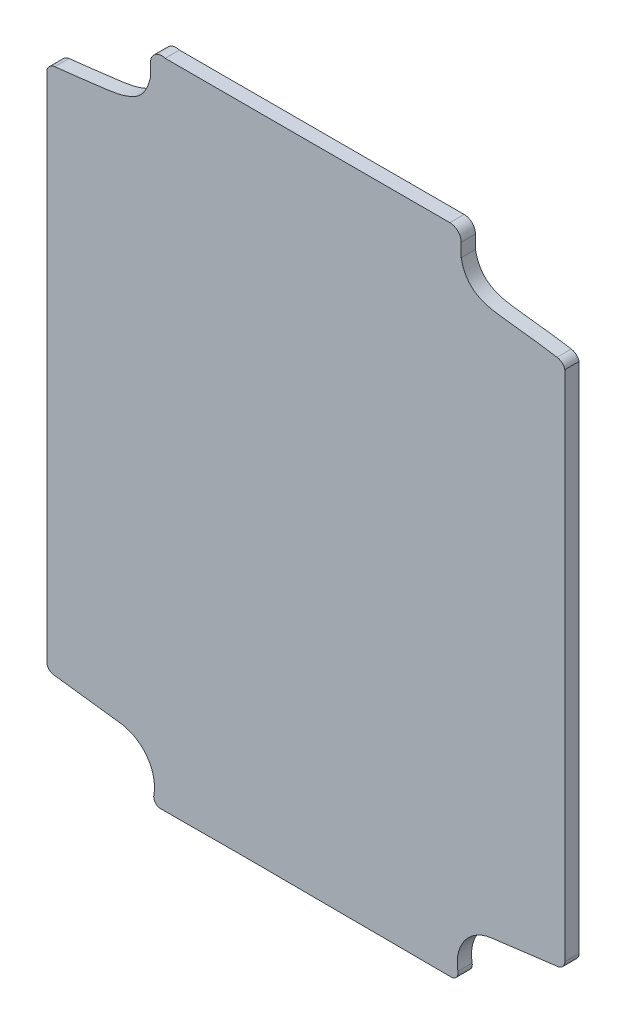
SolidWorks part; units mm, degrees
ref_plane "Front Plane" through (0, 0, 0) normal (0, 0, 1) x (1, 0, 0)
ref_plane "Top Plane" through (0, 0, 0) normal (0, 1, 0) x (1, 0, 0)
ref_plane "Right Plane" through (0, 0, 0) normal (1, 0, 0) x (0, 0, -1)
sketch "Sketch1" plane through (0, 0, 0) normal (0, 0, 1) x (1, 0, 0)
  line L0 (127, 465) -> (635, 465) construction
  line L3 (390.8841, 912.0626) -> (390.8841, 1148.9161) construction
  line L5 (213.6653, 879.6097) -> (572.9204, 879.6097)
  line L6 (587.1866, 865.3435) -> (587.1866, 848.4204)
  line L7 (717.9525, 791.5143) -> (717.9525, 144.5451)
  line L8 (708.0654, 134.658) -> (624.9414, 124.0917)
  line L9 (575.7917, 55.989) -> (311.2271, 57.05)
  line L11 (206.5649, 56.6303) -> (311.2271, 57.05)
  line L12 (74.2912, 135.2993) -> (157.4152, 124.733)
  line L13 (64.4041, 792.1556) -> (64.4041, 145.1863)
  line L14 (195.17, 865.9848) -> (195.17, 849.0616)
  line L20 (105.1835, 499.8417) -> (105.1835, 434.806) construction
  line L21 (87.257, 467.7407) -> (123.257, 467.7407) construction
  line L22 (98.7216, 499.8417) -> (111.6453, 499.8417)
  line L23 (98.7216, 434.806) -> (111.6453, 434.806)
  line L24 (111.6453, 499.8417) -> (111.6453, 484.2081)
  line L25 (98.7216, 499.8417) -> (98.7216, 484.2081)
  line L26 (98.7216, 434.806) -> (98.7216, 449.6058)
  line L27 (111.6453, 434.806) -> (111.6453, 449.6058)
  line L28 (683.0467, 434.806) -> (670.1229, 434.806)
  line L29 (683.0467, 499.8417) -> (670.1229, 499.8417)
  line L30 (683.0467, 434.806) -> (683.0467, 449.6058)
  line L31 (670.1229, 434.806) -> (670.1229, 449.6058)
  line L32 (670.1229, 499.8417) -> (670.1229, 484.2081)
  line L33 (683.0467, 499.8417) -> (683.0467, 484.2081)
  line L34 (654.6563, 466.9069) -> (698.2195, 466.9069) construction
  line L35 (423.0713, 104.5092) -> (423.0713, 91.5855)
  line L36 (358.0356, 104.5092) -> (358.0356, 91.5855)
  line L37 (423.0713, 104.5092) -> (408.2715, 104.5092)
  line L38 (423.0713, 91.5855) -> (408.2715, 91.5855)
  line L39 (358.0356, 91.5855) -> (373.6692, 91.5855)
  line L40 (358.0356, 104.5092) -> (373.6692, 104.5092)
  line L41 (423.2302, 842.8099) -> (423.2302, 829.8861)
  line L42 (358.1945, 842.8099) -> (358.1945, 829.8861)
  line L43 (423.2302, 842.8099) -> (408.4304, 842.8099)
  line L44 (423.2302, 829.8861) -> (408.4304, 829.8861)
  line L45 (358.1945, 829.8861) -> (373.8281, 829.8861)
  line L46 (358.1945, 842.8099) -> (373.8281, 842.8099)
  circle A0 centre (92.7885, 774.4272) radius 18
  circle A1 centre (153.2085, 765.7778) radius 18
  circle A2 centre (194.8311, 794.5037) radius 18
  circle A3 centre (236.8819, 848.4204) radius 18
  circle A5 centre (586.5052, 794.5037) radius 18
  circle A6 centre (628.2807, 765.7778) radius 18
  circle A7 centre (688.7549, 774.4272) radius 18
  circle A8 centre (544.9773, 848.4204) radius 18
  circle A9 centre (390.5346, 796.5425) radius 18
  circle A11 centre (92.7885, 159.2882) radius 18
  circle A12 centre (153.2085, 168.4793) radius 18
  circle A13 centre (194.8311, 139.5286) radius 18
  circle A15 centre (236.8819, 85.8518) radius 18
  circle A16 centre (544.9773, 85.8518) radius 18
  circle A17 centre (390.1739, 137.7924) radius 18
  circle A18 centre (586.5052, 139.5286) radius 18
  circle A20 centre (628.2807, 168.4793) radius 18
  circle A21 centre (688.7549, 159.2882) radius 18
  arc A22 (572.9204, 879.6097) -> (587.1866, 865.3435) centre (572.9204, 865.3435) cw
  arc A23 (708.0654, 800.1256) -> (717.9525, 791.5143) centre (706.4688, 788.3109) cw
  arc A24 (717.9525, 144.5451) -> (708.0654, 134.658) centre (708.0654, 144.5451) cw
  arc A25 (624.9414, 124.0917) -> (583.0081, 66.5315) centre (631.1129, 75.5412) ccw
  arc A26 (583.0081, 66.5315) -> (575.7917, 55.989) centre (574.1287, 64.8685) cw
  arc A27 (64.4041, 145.1863) -> (74.2912, 135.2993) centre (74.2912, 145.1863) ccw
  arc A28 (199.3485, 67.1728) -> (206.5649, 56.6303) centre (208.228, 65.5097) ccw
  arc A29 (157.4152, 124.733) -> (199.3485, 67.1728) centre (151.2437, 76.1824) cw
  arc A30 (74.2912, 800.7668) -> (64.4041, 792.1556) centre (75.8878, 788.9521) ccw
  arc A31 (213.6653, 879.6097) -> (195.17, 865.9848) centre (209.4362, 865.9848) ccw
  arc A32 (98.7216, 484.2081) -> (98.7216, 449.6058) centre (105.348, 466.9069) ccw
  arc A33 (111.6453, 484.2081) -> (111.6453, 449.6058) centre (105.0189, 466.9069) cw
  arc A34 (670.1229, 484.2081) -> (670.1229, 449.6058) centre (676.7494, 466.9069) ccw
  arc A35 (683.0467, 484.2081) -> (683.0467, 449.6058) centre (676.4202, 466.9069) cw
  circle A36 centre (148.6842, 466.9069) radius 18
  circle A37 centre (632.4423, 466.9069) radius 18
  arc A38 (373.6692, 91.5855) -> (408.2715, 91.5855) centre (390.9703, 98.2119) ccw
  arc A39 (373.6692, 104.5092) -> (408.2715, 104.5092) centre (390.9703, 97.8828) cw
  arc A40 (373.8281, 829.8861) -> (408.4304, 829.8861) centre (391.1292, 836.5126) ccw
  arc A41 (373.8281, 842.8099) -> (408.4304, 842.8099) centre (391.1292, 836.1834) cw
  spline S0 degree 3 poles (134.7471, 211.4176) (152.8168, 198.2285) (173.4297, 194.7237) (206.2799, 204.2352) (218.6001, 238.403) (215.0005, 157.9272) (261.6667, 159.9838) (283.8241, 199.2804) (314.2323, 230.1149) (305.2971, 269.6637) (285.2096, 294.946) (231.9509, 299.4798) (212.9045, 263.7426) (209.9318, 280.2662) (190.1646, 292.7397) (159.7593, 299.5382) (121.7886, 279.8173) (117.8446, 233.2785) (134.7471, 211.4176) (152.8168, 198.2285) (173.4297, 194.7237) knots -0.133764 -0.081828 -0.041908 0 0.04195 0.101208 0.155786 0.286134 0.362687 0.379278 0.452042 0.533513 0.593085 0.660805 0.699095 0.73753 0.75625 0.796881 0.866236 0.918172 0.958092 1 1.04195 1.101208 1.155786 only from (152.7697, 199.9518) to (152.7697, 199.9518)
  spline S1 degree 3 poles (135.1859, 721.7604) (153.2557, 734.9495) (173.8685, 738.4543) (206.7187, 728.9429) (219.0389, 694.7751) (215.4393, 775.2509) (262.1055, 773.1942) (284.2629, 733.8977) (314.6712, 703.0631) (305.736, 663.5143) (285.6484, 638.2321) (232.3897, 633.6982) (213.3433, 669.4354) (210.3706, 652.9118) (190.6035, 640.4383) (160.1982, 633.6398) (122.2275, 653.3608) (118.2834, 699.8995) (135.1859, 721.7604) (153.2557, 734.9495) (173.8685, 738.4543) knots -0.133764 -0.081828 -0.041908 0 0.04195 0.101208 0.155786 0.286134 0.362687 0.379278 0.452042 0.533513 0.593085 0.660805 0.699095 0.73753 0.75625 0.796881 0.866236 0.918172 0.958092 1 1.04195 1.101208 1.155786 only from (153.2085, 733.2263) to (153.2085, 733.2263)
  spline S2 degree 3 poles (645.9427, 212.0915) (627.8729, 198.9024) (607.26, 195.3976) (574.4098, 204.9091) (562.0897, 239.0769) (565.6892, 158.6011) (519.0231, 160.6577) (496.8656, 199.9543) (466.4574, 230.7889) (475.3926, 270.3377) (495.4801, 295.6199) (548.7388, 300.1538) (567.7852, 264.4165) (570.7579, 280.9402) (590.5251, 293.4137) (620.9304, 300.2122) (658.9011, 280.4912) (662.8452, 233.9524) (645.9427, 212.0915) (627.8729, 198.9024) (607.26, 195.3976) knots -0.133764 -0.081828 -0.041908 0 0.04195 0.101208 0.155786 0.286134 0.362687 0.379278 0.452042 0.533513 0.593085 0.660805 0.699095 0.73753 0.75625 0.796881 0.866236 0.918172 0.958092 1 1.04195 1.101208 1.155786 only from (627.92, 200.6257) to (627.92, 200.6257)
  spline S3 degree 3 poles (646.5422, 722.3875) (628.4724, 735.5766) (607.8596, 739.0814) (575.0094, 729.5699) (562.6892, 695.4022) (566.2888, 775.878) (519.6226, 773.8213) (497.4652, 734.5248) (467.0569, 703.6902) (475.9921, 664.1414) (496.0797, 638.8592) (549.3384, 634.3253) (568.3848, 670.0625) (571.3575, 653.5389) (591.1246, 641.0654) (621.5299, 634.2669) (659.5006, 653.9879) (663.4447, 700.5266) (646.5422, 722.3875) (628.4724, 735.5766) (607.8596, 739.0814) knots -0.133764 -0.081828 -0.041908 0 0.04195 0.101208 0.155786 0.286134 0.362687 0.379278 0.452042 0.533513 0.593085 0.660805 0.699095 0.73753 0.75625 0.796881 0.866236 0.918172 0.958092 1 1.04195 1.101208 1.155786 only from (628.5196, 733.8534) to (628.5196, 733.8534)
  spline S4 degree 3 poles (195.17, 849.0616) (190.0076, 829.9692) (180.5238, 818.7484) (154.3908, 810.5337) (101.8412, 803.5005) (88.1469, 802.6392) (74.2912, 800.7668) knots 0 0 0 0 0.202419 0.278084 0.357842 1 1 1 1
  spline S6 degree 3 poles (587.1866, 848.4204) (591.8291, 824.0333) (611.9997, 812.1812) (684.5998, 804.295) (694.2097, 801.998) (708.0654, 800.1256) knots 0 0 0 0 0.276269 0.356159 1 1 1 1
  point P147 (393.2928, 879.6097)
  point P148 (105.1835, 467.3238)
  point P152 (105.1835, 499.8417)
  point P155 (105.1835, 434.806)
  point P167 (676.5848, 434.806)
  point P174 (676.5848, 499.8417)
extrude "Boss-Extrude4" add sketch "Sketch1" along normal blind 18 contours A27 L12 A29 A28 L11 L9 A26 A25 L8 A24 L7 A23 S6 L6 A22 L5 A31 L14 S4 A30 L13
sketch "Sketch6" plane through (0, 0, 0) normal (0, 0, 1) x (1, 0, 0)
  line L0 (127, 465) -> (635, 465) construction
  line L3 (390.8841, 912.0626) -> (390.8841, 1148.9161) construction
  line L5 (213.6653, 879.6097) -> (572.9204, 879.6097)
  line L6 (587.1866, 865.3435) -> (587.1866, 848.4204)
  line L7 (717.9525, 791.5143) -> (717.9525, 144.5451)
  line L8 (708.0654, 134.658) -> (624.9414, 124.0917)
  line L9 (575.7917, 55.989) -> (311.2271, 57.05)
  line L11 (206.5649, 56.6303) -> (311.2271, 57.05)
  line L12 (74.2912, 135.2993) -> (157.4152, 124.733)
  line L13 (64.4041, 792.1556) -> (64.4041, 145.1863)
  line L14 (195.17, 865.9848) -> (195.17, 849.0616)
  line L20 (105.1835, 499.8417) -> (105.1835, 434.806) construction
  line L21 (87.257, 467.7407) -> (123.257, 467.7407) construction
  line L22 (98.7216, 499.8417) -> (111.6453, 499.8417)
  line L23 (98.7216, 434.806) -> (111.6453, 434.806)
  line L24 (111.6453, 499.8417) -> (111.6453, 484.2081)
  line L25 (98.7216, 499.8417) -> (98.7216, 484.2081)
  line L26 (98.7216, 434.806) -> (98.7216, 449.6058)
  line L27 (111.6453, 434.806) -> (111.6453, 449.6058)
  line L28 (683.0467, 434.806) -> (670.1229, 434.806)
  line L29 (683.0467, 499.8417) -> (670.1229, 499.8417)
  line L30 (683.0467, 434.806) -> (683.0467, 449.6058)
  line L31 (670.1229, 434.806) -> (670.1229, 449.6058)
  line L32 (670.1229, 499.8417) -> (670.1229, 484.2081)
  line L33 (683.0467, 499.8417) -> (683.0467, 484.2081)
  line L34 (654.6563, 466.9069) -> (698.2195, 466.9069) construction
  line L35 (423.0713, 104.5092) -> (423.0713, 91.5855)
  line L36 (358.0356, 104.5092) -> (358.0356, 91.5855)
  line L37 (423.0713, 104.5092) -> (408.2715, 104.5092)
  line L38 (423.0713, 91.5855) -> (408.2715, 91.5855)
  line L39 (358.0356, 91.5855) -> (373.6692, 91.5855)
  line L40 (358.0356, 104.5092) -> (373.6692, 104.5092)
  line L41 (423.2302, 842.8099) -> (423.2302, 829.8861)
  line L42 (358.1945, 842.8099) -> (358.1945, 829.8861)
  line L43 (423.2302, 842.8099) -> (408.4304, 842.8099)
  line L44 (423.2302, 829.8861) -> (408.4304, 829.8861)
  line L45 (358.1945, 829.8861) -> (373.8281, 829.8861)
  line L46 (358.1945, 842.8099) -> (373.8281, 842.8099)
  circle A0 centre (92.7885, 774.4272) radius 18
  circle A1 centre (153.2085, 765.7778) radius 18
  circle A2 centre (194.8311, 794.5037) radius 18
  circle A3 centre (236.8819, 848.4204) radius 18
  circle A5 centre (586.5052, 794.5037) radius 18
  circle A6 centre (628.2807, 765.7778) radius 18
  circle A7 centre (688.7549, 774.4272) radius 18
  circle A8 centre (544.9773, 848.4204) radius 18
  circle A9 centre (390.5346, 796.5425) radius 18
  circle A11 centre (92.7885, 159.2882) radius 18
  circle A12 centre (153.2085, 168.4793) radius 18
  circle A13 centre (194.8311, 139.5286) radius 18
  circle A15 centre (236.8819, 85.8518) radius 18
  circle A16 centre (544.9773, 85.8518) radius 18
  circle A17 centre (390.1739, 137.7924) radius 18
  circle A18 centre (586.5052, 139.5286) radius 18
  circle A20 centre (628.2807, 168.4793) radius 18
  circle A21 centre (688.7549, 159.2882) radius 18
  arc A22 (572.9204, 879.6097) -> (587.1866, 865.3435) centre (572.9204, 865.3435) cw
  arc A23 (708.0654, 800.1256) -> (717.9525, 791.5143) centre (706.4688, 788.3109) cw
  arc A24 (717.9525, 144.5451) -> (708.0654, 134.658) centre (708.0654, 144.5451) cw
  arc A25 (624.9414, 124.0917) -> (583.0081, 66.5315) centre (631.1129, 75.5412) ccw
  arc A26 (583.0081, 66.5315) -> (575.7917, 55.989) centre (574.1287, 64.8685) cw
  arc A27 (64.4041, 145.1863) -> (74.2912, 135.2993) centre (74.2912, 145.1863) ccw
  arc A28 (199.3485, 67.1728) -> (206.5649, 56.6303) centre (208.228, 65.5097) ccw
  arc A29 (157.4152, 124.733) -> (199.3485, 67.1728) centre (151.2437, 76.1824) cw
  arc A30 (74.2912, 800.7668) -> (64.4041, 792.1556) centre (75.8878, 788.9521) ccw
  arc A31 (213.6653, 879.6097) -> (195.17, 865.9848) centre (209.4362, 865.9848) ccw
  arc A32 (98.7216, 484.2081) -> (98.7216, 449.6058) centre (105.348, 466.9069) ccw
  arc A33 (111.6453, 484.2081) -> (111.6453, 449.6058) centre (105.0189, 466.9069) cw
  arc A34 (670.1229, 484.2081) -> (670.1229, 449.6058) centre (676.7494, 466.9069) ccw
  arc A35 (683.0467, 484.2081) -> (683.0467, 449.6058) centre (676.4202, 466.9069) cw
  circle A36 centre (148.6842, 466.9069) radius 18
  circle A37 centre (632.4423, 466.9069) radius 18
  arc A38 (373.6692, 91.5855) -> (408.2715, 91.5855) centre (390.9703, 98.2119) ccw
  arc A39 (373.6692, 104.5092) -> (408.2715, 104.5092) centre (390.9703, 97.8828) cw
  arc A40 (373.8281, 829.8861) -> (408.4304, 829.8861) centre (391.1292, 836.5126) ccw
  arc A41 (373.8281, 842.8099) -> (408.4304, 842.8099) centre (391.1292, 836.1834) cw
  spline S0 degree 3 poles (134.7471, 211.4176) (152.8168, 198.2285) (173.4297, 194.7237) (206.2799, 204.2352) (218.6001, 238.403) (215.0005, 157.9272) (261.6667, 159.9838) (283.8241, 199.2804) (314.2323, 230.1149) (305.2971, 269.6637) (285.2096, 294.946) (231.9509, 299.4798) (212.9045, 263.7426) (209.9318, 280.2662) (190.1646, 292.7397) (159.7593, 299.5382) (121.7886, 279.8173) (117.8446, 233.2785) (134.7471, 211.4176) (152.8168, 198.2285) (173.4297, 194.7237) knots -0.133764 -0.081828 -0.041908 0 0.04195 0.101208 0.155786 0.286134 0.362687 0.379278 0.452042 0.533513 0.593085 0.660805 0.699095 0.73753 0.75625 0.796881 0.866236 0.918172 0.958092 1 1.04195 1.101208 1.155786 only from (152.7697, 199.9518) to (152.7697, 199.9518)
  spline S1 degree 3 poles (135.1859, 721.7604) (153.2557, 734.9495) (173.8685, 738.4543) (206.7187, 728.9429) (219.0389, 694.7751) (215.4393, 775.2509) (262.1055, 773.1942) (284.2629, 733.8977) (314.6712, 703.0631) (305.736, 663.5143) (285.6484, 638.2321) (232.3897, 633.6982) (213.3433, 669.4354) (210.3706, 652.9118) (190.6035, 640.4383) (160.1982, 633.6398) (122.2275, 653.3608) (118.2834, 699.8995) (135.1859, 721.7604) (153.2557, 734.9495) (173.8685, 738.4543) knots -0.133764 -0.081828 -0.041908 0 0.04195 0.101208 0.155786 0.286134 0.362687 0.379278 0.452042 0.533513 0.593085 0.660805 0.699095 0.73753 0.75625 0.796881 0.866236 0.918172 0.958092 1 1.04195 1.101208 1.155786 only from (153.2085, 733.2263) to (153.2085, 733.2263)
  spline S2 degree 3 poles (645.9427, 212.0915) (627.8729, 198.9024) (607.26, 195.3976) (574.4098, 204.9091) (562.0897, 239.0769) (565.6892, 158.6011) (519.0231, 160.6577) (496.8656, 199.9543) (466.4574, 230.7889) (475.3926, 270.3377) (495.4801, 295.6199) (548.7388, 300.1538) (567.7852, 264.4165) (570.7579, 280.9402) (590.5251, 293.4137) (620.9304, 300.2122) (658.9011, 280.4912) (662.8452, 233.9524) (645.9427, 212.0915) (627.8729, 198.9024) (607.26, 195.3976) knots -0.133764 -0.081828 -0.041908 0 0.04195 0.101208 0.155786 0.286134 0.362687 0.379278 0.452042 0.533513 0.593085 0.660805 0.699095 0.73753 0.75625 0.796881 0.866236 0.918172 0.958092 1 1.04195 1.101208 1.155786 only from (627.92, 200.6257) to (627.92, 200.6257)
  spline S3 degree 3 poles (646.5422, 722.3875) (628.4724, 735.5766) (607.8596, 739.0814) (575.0094, 729.5699) (562.6892, 695.4022) (566.2888, 775.878) (519.6226, 773.8213) (497.4652, 734.5248) (467.0569, 703.6902) (475.9921, 664.1414) (496.0797, 638.8592) (549.3384, 634.3253) (568.3848, 670.0625) (571.3575, 653.5389) (591.1246, 641.0654) (621.5299, 634.2669) (659.5006, 653.9879) (663.4447, 700.5266) (646.5422, 722.3875) (628.4724, 735.5766) (607.8596, 739.0814) knots -0.133764 -0.081828 -0.041908 0 0.04195 0.101208 0.155786 0.286134 0.362687 0.379278 0.452042 0.533513 0.593085 0.660805 0.699095 0.73753 0.75625 0.796881 0.866236 0.918172 0.958092 1 1.04195 1.101208 1.155786 only from (628.5196, 733.8534) to (628.5196, 733.8534)
  spline S4 degree 3 poles (195.17, 849.0616) (190.0076, 829.9692) (180.5238, 818.7484) (154.3908, 810.5337) (101.8412, 803.5005) (88.1469, 802.6392) (74.2912, 800.7668) knots 0 0 0 0 0.202419 0.278084 0.357842 1 1 1 1
  spline S6 degree 3 poles (587.1866, 848.4204) (591.8291, 824.0333) (611.9997, 812.1812) (684.5998, 804.295) (694.2097, 801.998) (708.0654, 800.1256) knots 0 0 0 0 0.276269 0.356159 1 1 1 1
  point P147 (393.2928, 879.6097)
  point P148 (105.1835, 467.3238)
  point P152 (105.1835, 499.8417)
  point P155 (105.1835, 434.806)
  point P167 (676.5848, 434.806)
  point P174 (676.5848, 499.8417)
extrude "Cut-Extrude3" cut sketch "Sketch6" along normal blind 8 contours S3 | A7 | A6 | A5 | A8 | A41 L46 L42 L45 A40 L44 L41 L43 | A9 | A3 | A2 | S1 | A1 | A0 | A35 L33 L29 L32 A34 L31 L28 L30 | A37 | A36 | S0 | S2 | A16 | A18 | A20 | A21 | A17 | A39 L40 L36 L39 A38 L38 L35 L37 | A15 | A13 | A12 | A11 | A32 L26 L23 L27 A33 L24 L22 L25
